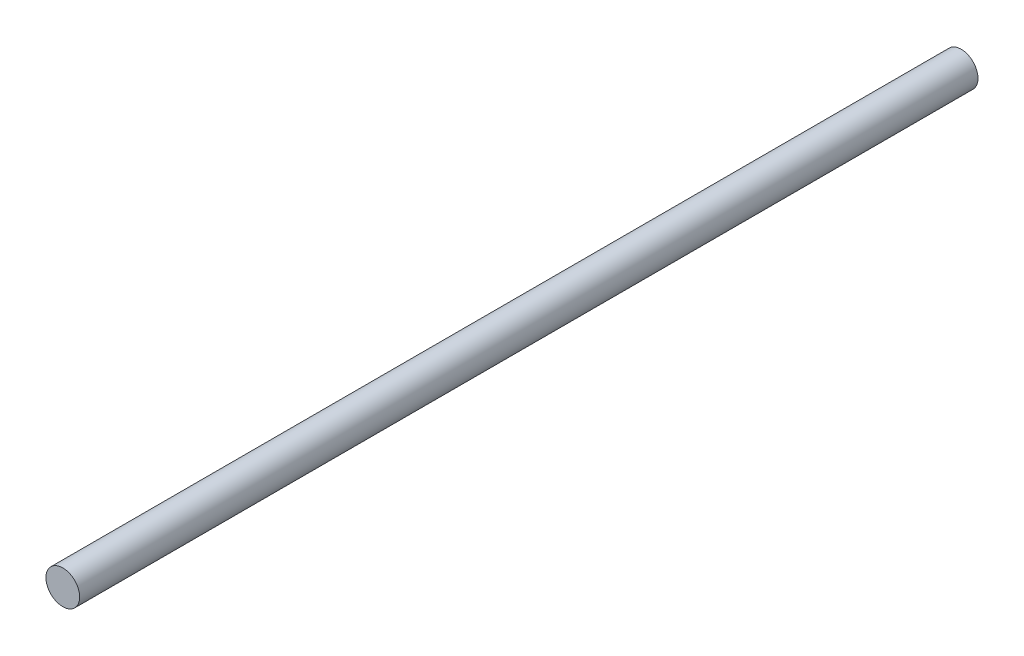
SolidWorks part; units mm, degrees
ref_plane "前视基准面" through (0, 0, 0) normal (0, 0, 1) x (1, 0, 0)
ref_plane "上视基准面" through (0, 0, 0) normal (0, 1, 0) x (1, 0, 0)
ref_plane "右视基准面" through (0, 0, 0) normal (1, 0, 0) x (0, 0, -1)
sketch "草图1" plane through (0, 0, 0) normal (0, 0, 1) x (1, 0, 0)
  circle A0 centre (0, 0) radius 3
  dimension "D1" = 6
extrude "凸台-拉伸1" add sketch "草图1" along normal blind 160
